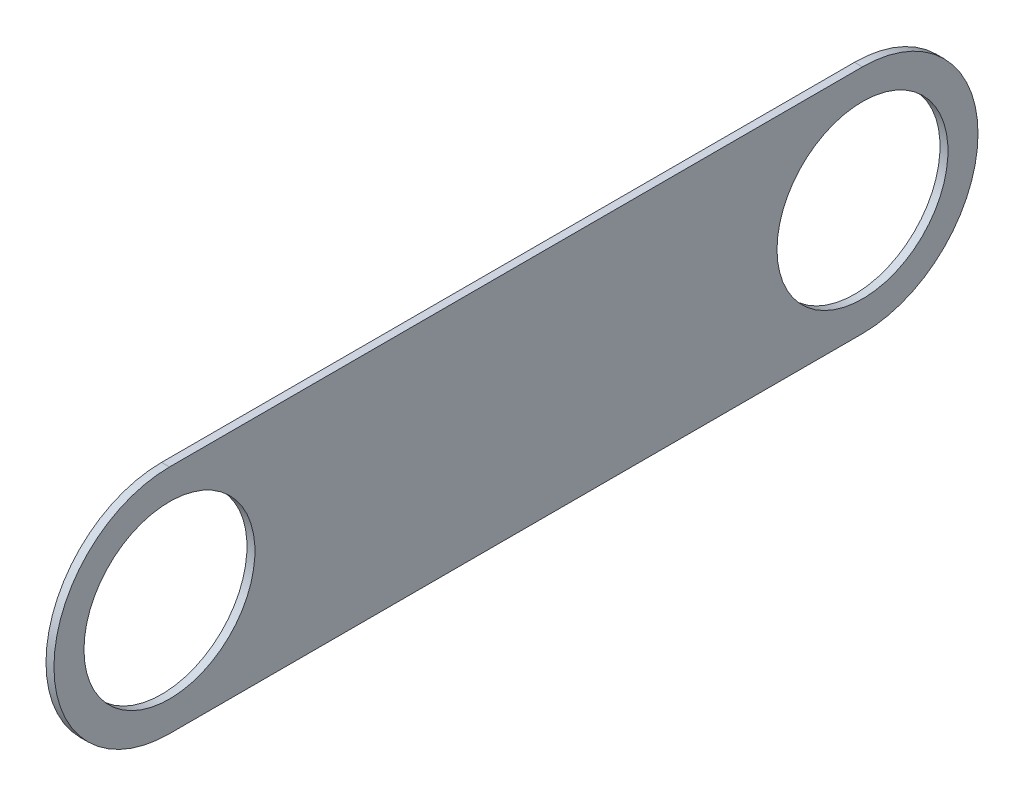
SolidWorks part; units mm, degrees
material "6061-T6 (SS)"
ref_plane "Front Plane" through (0, 0, 0) normal (1, 0, 0) x (0, 1, 0)
ref_plane "Top Plane" through (0, 0, 0) normal (0, 0, 1) x (0, 1, 0)
ref_plane "Right Plane" through (0, 0, 0) normal (0, 1, 0) x (-1, 0, 0)
sketch "Sketch1" plane through (0, 0, 0) normal (1, 0, 0) x (0, 1, 0)
  line L0 (0, 0) -> (0, 76.2)
  line L2 (25.4, 76.2) -> (25.4, 0)
  arc A0 (25.4, 76.2) -> (0, 76.2) centre (12.7, 76.2) ccw
  arc A1 (0, 0) -> (25.4, 0) centre (12.7, 0) ccw
  dimension "D3" = 12.7
  dimension "D1" = 76.2
  dimension "D2" = 25.4
extrude "Boss-Extrude1" add sketch "Sketch1" along normal blind 0.8738
sketch "Sketch2" plane through (0, 0, 0) normal (1, 0, 0) x (0, 1, 0)
  circle A0 centre (12.7, 76.2) radius 9.398
  circle A1 centre (12.7, 0) radius 9.398
extrude "Cut-Extrude1" cut sketch "Sketch2" along normal blind 0.8738
equation "\"Width\"= .03"
equation "\"Link Diameter\"=1"
equation "\"Link Radius\"= \"Link Diameter\" / 2"
equation "\"Length\"= 3"
equation "\"Bracket Diameter w/ Tol\"= .37"
equation "\"D1@Sketch1\"=\"Length\""
equation "\"D3@Sketch1\"=\"Link Radius\""
